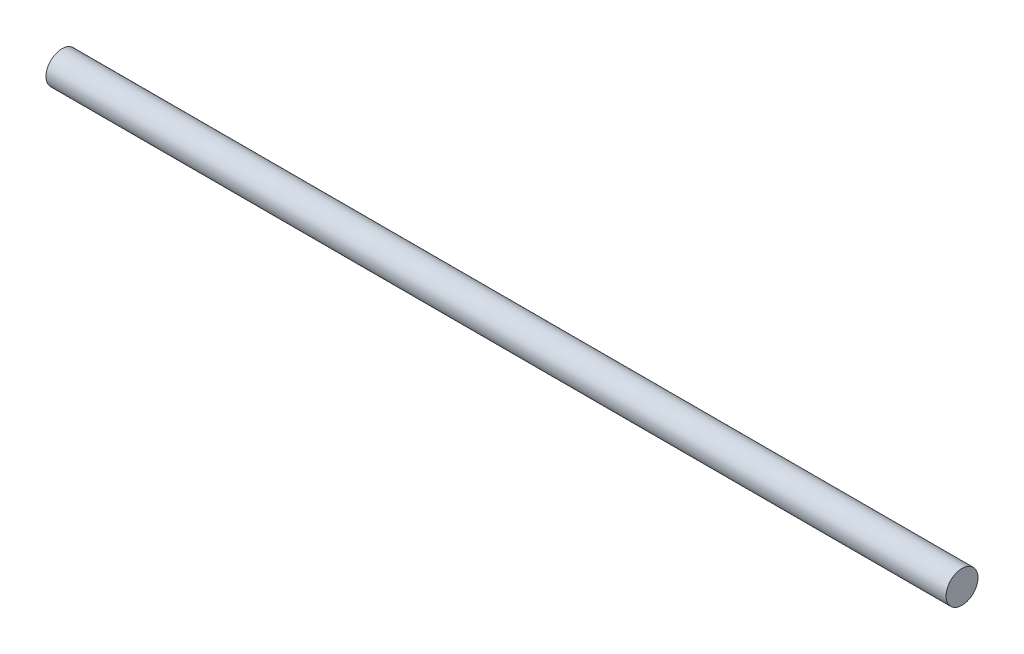
SolidWorks part; units mm, degrees
material "Copper"
ref_plane "Front Plane" through (0, 0, 0) normal (0, 0, 1) x (1, 0, 0)
ref_plane "Top Plane" through (0, 0, 0) normal (0, 1, 0) x (1, 0, 0)
ref_plane "Right Plane" through (0, 0, 0) normal (1, 0, 0) x (0, 0, -1)
sketch "Sketch1" plane through (0, 0, 0) normal (1, 0, 0) x (0, 0, -1)
  circle A0 centre (0, 0) radius 0.1775
  dimension "D1" = 0.355
extrude "Boss-Extrude1" add sketch "Sketch1" along normal mid plane 10
